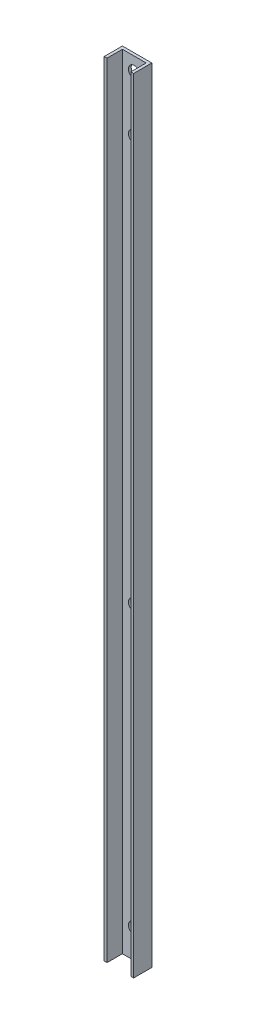
SolidWorks part; units mm, degrees
ref_plane "Front Plane" through (0, 0, 0) normal (0, 0, 1) x (1, 0, 0)
ref_plane "Top Plane" through (0, 0, 0) normal (0, 1, 0) x (1, 0, 0)
ref_plane "Right Plane" through (0, 0, 0) normal (1, 0, 0) x (0, 0, -1)
sketch "Sketch1" plane through (0, 0, 0) normal (0, 1, 0) x (1, 0, 0)
  line L0 (-3.47, -1.8133) -> (-3.47, 4.6867)
  line L1 (-3.47, 4.6867) -> (7.03, 4.6867)
  line L2 (7.03, 4.6867) -> (7.03, -1.8133)
  dimension "D1" = 10.5
  dimension "D2" = 6.5
  dimension "D3" = 6.5
extrude "Extrude-Thin1" add sketch "Sketch1" along normal blind 280 thin
sketch "Sketch2" plane through (0, 0, -4.6867) normal (0, 0, -1) x (-1, 0, 0)
  circle A0 centre (-1.78, 275) radius 2.1
  circle A1 centre (-1.78, 255) radius 2.1
  circle A2 centre (-1.78, 275) radius 2.1 construction
  circle A3 centre (-1.78, 255) radius 2.1 construction
  circle A4 centre (-1.78, 110) radius 2.1
  circle A5 centre (-1.78, 10) radius 2.1
  dimension "D1" = 4.2
  dimension "D2" = 4.2
extrude "Cut-Extrude1" cut sketch "Sketch2" against normal blind 10
